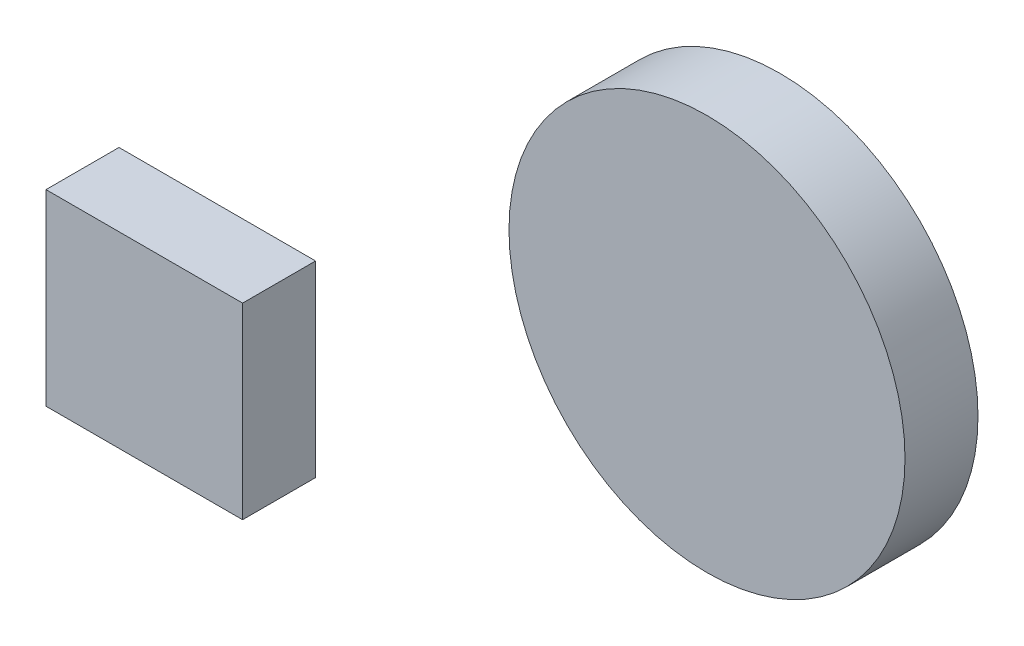
SolidWorks part; units mm, degrees
ref_plane "前视基准面" through (0, 0, 0) normal (0, 0, 1) x (1, 0, 0)
ref_plane "上视基准面" through (0, 0, 0) normal (0, 1, 0) x (1, 0, 0)
ref_plane "右视基准面" through (0, 0, 0) normal (1, 0, 0) x (0, 0, -1)
other "Configuration Table"
sketch "Sketch1" plane through (0, 0, 0) normal (0, 0, 1) x (1, 0, 0)
  circle A0 centre (34.3129, 34.4571) radius 27.1249
extrude "Boss-Extrude1" add sketch "Sketch1" along normal blind 10
sketch "Sketch2" plane through (0, 0, 10) normal (0, 0, 1) x (1, 0, 0)
  line L1 (-46.2358, 17.5092) -> (-19.305, 17.5092)
  line L2 (-46.2358, 17.5092) -> (-46.2358, -8.1932)
  line L3 (-46.2358, -8.1932) -> (-19.305, -8.1932)
  line L4 (-19.305, 17.5092) -> (-19.305, -8.1932)
extrude "Boss-Extrude2" add sketch "Sketch2" along normal blind 10 separate body
